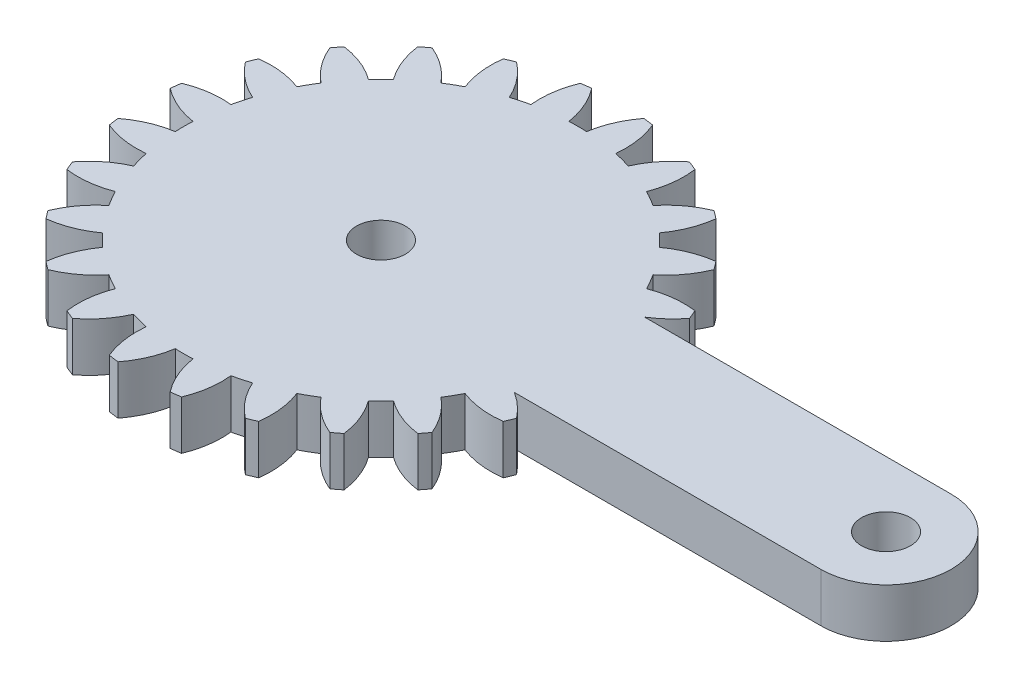
SolidWorks part; units mm, degrees
ref_plane "Front Plane" through (0, 0, 0) normal (0, 0, 1) x (1, 0, 0)
ref_plane "Top Plane" through (0, 0, 0) normal (0, 1, 0) x (1, 0, 0)
ref_plane "Right Plane" through (0, 0, 0) normal (1, 0, 0) x (0, 0, -1)
sketch "Sketch1" plane through (0, 0, 0) normal (0, 1, 0) x (1, 0, 0)
  line L0 (20.8937, 4) -> (2.0816, 4)
  line L1 (2.0816, -4) -> (20.8937, -4)
  line L2 (20.8937, 0) -> (-10.1063, 0) construction
  arc A0 (2.0816, 4) -> (3.5217, 5.3071) centre (-0.7683, 8.5867) ccw
  arc A1 (3.5217, 5.3071) -> (3.2829, 5.8838) centre (-10.1063, 0) ccw
  arc A2 (3.2829, 5.8838) -> (0.6271, 5.5703) centre (2.5684, 0.5313) ccw
  arc A3 (0.6271, 5.5703) -> (0.0844, 6.5103) centre (-10.1063, 0) ccw
  arc A4 (0.0844, 6.5103) -> (1.6838, 8.6535) centre (-3.3089, 10.711) ccw
  arc A5 (1.6838, 8.6535) -> (1.3038, 9.1487) centre (-10.1063, 0) ccw
  arc A6 (1.3038, 9.1487) -> (-1.1803, 8.1585) centre (1.999, 3.7936) ccw
  arc A7 (-1.1803, 8.1585) -> (-1.9479, 8.926) centre (-10.1063, 0) ccw
  arc A8 (-1.9479, 8.926) -> (-0.9576, 11.4102) centre (-6.3127, 12.1053) ccw
  arc A9 (-0.9576, 11.4102) -> (-1.4528, 11.7901) centre (-10.1063, 0) ccw
  arc A10 (-1.4528, 11.7901) -> (-3.596, 10.1907) centre (0.6046, 6.7975) ccw
  arc A11 (-3.596, 10.1907) -> (-4.5361, 10.7334) centre (-10.1063, 0) ccw
  arc A12 (-4.5361, 10.7334) -> (-4.2225, 13.3892) centre (-9.5751, 12.6747) ccw
  arc A13 (-4.2225, 13.3892) -> (-4.7992, 13.6281) centre (-10.1063, 0) ccw
  arc A14 (-4.7992, 13.6281) -> (-6.4554, 11.5285) centre (-1.5196, 9.3381) ccw
  arc A15 (-6.4554, 11.5285) -> (-7.5039, 11.8094) centre (-10.1063, 0) ccw
  arc A16 (-7.5039, 11.8094) -> (-7.8884, 14.4558) centre (-12.8736, 12.3803) ccw
  arc A17 (-7.8884, 14.4558) -> (-8.5072, 14.5373) centre (-10.1063, 0) ccw
  arc A18 (-8.5072, 14.5373) -> (-9.5636, 12.0806) centre (-4.2291, 11.2423) ccw
  arc A19 (-9.5636, 12.0806) -> (-10.6491, 12.0806) centre (-10.1063, 0) ccw
  arc A20 (-10.6491, 12.0806) -> (-11.7054, 14.5373) centre (-15.9836, 11.2423) ccw
  arc A21 (-11.7054, 14.5373) -> (-12.3243, 14.4558) centre (-10.1063, 0) ccw
  arc A22 (-12.3243, 14.4558) -> (-12.7088, 11.8094) centre (-7.3391, 12.3803) ccw
  arc A23 (-12.7088, 11.8094) -> (-13.7573, 11.5285) centre (-10.1063, 0) ccw
  arc A24 (-13.7573, 11.5285) -> (-15.4135, 13.6281) centre (-18.6931, 9.3381) ccw
  arc A25 (-15.4135, 13.6281) -> (-15.9901, 13.3892) centre (-10.1063, 0) ccw
  arc A26 (-15.9901, 13.3892) -> (-15.6766, 10.7334) centre (-10.6376, 12.6747) ccw
  arc A27 (-15.6766, 10.7334) -> (-16.6166, 10.1907) centre (-10.1063, 0) ccw
  arc A28 (-16.6166, 10.1907) -> (-18.7599, 11.7901) centre (-20.8173, 6.7975) ccw
  arc A29 (-18.7599, 11.7901) -> (-19.255, 11.4102) centre (-10.1063, 0) ccw
  arc A30 (-19.255, 11.4102) -> (-18.2648, 8.926) centre (-13.9, 12.1053) ccw
  arc A31 (-18.2648, 8.926) -> (-19.0324, 8.1585) centre (-10.1063, 0) ccw
  arc A32 (-19.0324, 8.1585) -> (-21.5165, 9.1487) centre (-22.2117, 3.7936) ccw
  arc A33 (-21.5165, 9.1487) -> (-21.8965, 8.6535) centre (-10.1063, 0) ccw
  arc A34 (-21.8965, 8.6535) -> (-20.2971, 6.5103) centre (-16.9038, 10.711) ccw
  arc A35 (-20.2971, 6.5103) -> (-20.8398, 5.5703) centre (-10.1063, 0) ccw
  arc A36 (-20.8398, 5.5703) -> (-23.4956, 5.8838) centre (-22.7811, 0.5313) ccw
  arc A37 (-23.4956, 5.8838) -> (-23.7344, 5.3071) centre (-10.1063, 0) ccw
  arc A38 (-23.7344, 5.3071) -> (-21.6348, 3.6509) centre (-19.4444, 8.5867) ccw
  arc A39 (-21.6348, 3.6509) -> (-21.9157, 2.6025) centre (-10.1063, 0) ccw
  arc A40 (-21.9157, 2.6025) -> (-24.5622, 2.2179) centre (-22.4867, -2.7673) ccw
  arc A41 (-24.5622, 2.2179) -> (-24.6437, 1.5991) centre (-10.1063, 0) ccw
  arc A42 (-24.6437, 1.5991) -> (-22.1869, 0.5427) centre (-21.3486, 5.8773) ccw
  arc A43 (-22.1869, 0.5427) -> (-22.1869, -0.5427) centre (-10.1063, 0) ccw
  arc A44 (-22.1869, -0.5427) -> (-24.6437, -1.5991) centre (-21.3486, -5.8773) ccw
  arc A45 (-24.6437, -1.5991) -> (-24.5622, -2.2179) centre (-10.1063, 0) ccw
  arc A46 (-24.5622, -2.2179) -> (-21.9157, -2.6025) centre (-22.4867, 2.7673) ccw
  arc A47 (-21.9157, -2.6025) -> (-21.6348, -3.6509) centre (-10.1063, 0) ccw
  arc A48 (-21.6348, -3.6509) -> (-23.7344, -5.3071) centre (-19.4444, -8.5867) ccw
  arc A49 (-23.7344, -5.3071) -> (-23.4956, -5.8838) centre (-10.1063, 0) ccw
  arc A50 (-23.4956, -5.8838) -> (-20.8398, -5.5703) centre (-22.7811, -0.5313) ccw
  arc A51 (-20.8398, -5.5703) -> (-20.2971, -6.5103) centre (-10.1063, 0) ccw
  arc A52 (-20.2971, -6.5103) -> (-21.8965, -8.6535) centre (-16.9038, -10.711) ccw
  arc A53 (-21.8965, -8.6535) -> (-21.5165, -9.1487) centre (-10.1063, 0) ccw
  arc A54 (-21.5165, -9.1487) -> (-19.0324, -8.1585) centre (-22.2117, -3.7936) ccw
  arc A55 (-19.0324, -8.1585) -> (-18.2648, -8.926) centre (-10.1063, 0) ccw
  arc A56 (-18.2648, -8.926) -> (-19.255, -11.4102) centre (-13.9, -12.1053) ccw
  arc A57 (-19.255, -11.4102) -> (-18.7599, -11.7901) centre (-10.1063, 0) ccw
  arc A58 (-18.7599, -11.7901) -> (-16.6166, -10.1907) centre (-20.8173, -6.7975) ccw
  arc A59 (-16.6166, -10.1907) -> (-15.6766, -10.7334) centre (-10.1063, 0) ccw
  arc A60 (-15.6766, -10.7334) -> (-15.9901, -13.3892) centre (-10.6376, -12.6747) ccw
  arc A61 (-15.9901, -13.3892) -> (-15.4135, -13.6281) centre (-10.1063, 0) ccw
  arc A62 (-15.4135, -13.6281) -> (-13.7573, -11.5285) centre (-18.6931, -9.3381) ccw
  arc A63 (-13.7573, -11.5285) -> (-12.7088, -11.8094) centre (-10.1063, 0) ccw
  arc A64 (-12.7088, -11.8094) -> (-12.3243, -14.4558) centre (-7.3391, -12.3803) ccw
  arc A65 (-12.3243, -14.4558) -> (-11.7054, -14.5373) centre (-10.1063, 0) ccw
  arc A66 (-11.7054, -14.5373) -> (-10.6491, -12.0806) centre (-15.9836, -11.2423) ccw
  arc A67 (-10.6491, -12.0806) -> (-9.5636, -12.0806) centre (-10.1063, 0) ccw
  arc A68 (-9.5636, -12.0806) -> (-8.5072, -14.5373) centre (-4.2291, -11.2423) ccw
  arc A69 (-8.5072, -14.5373) -> (-7.8884, -14.4558) centre (-10.1063, 0) ccw
  arc A70 (-7.8884, -14.4558) -> (-7.5039, -11.8094) centre (-12.8736, -12.3803) ccw
  arc A71 (-7.5039, -11.8094) -> (-6.4554, -11.5285) centre (-10.1063, 0) ccw
  arc A72 (-6.4554, -11.5285) -> (-4.7992, -13.6281) centre (-1.5196, -9.3381) ccw
  arc A73 (-4.7992, -13.6281) -> (-4.2225, -13.3892) centre (-10.1063, 0) ccw
  arc A74 (-4.2225, -13.3892) -> (-4.5361, -10.7334) centre (-9.5751, -12.6747) ccw
  arc A75 (-4.5361, -10.7334) -> (-3.596, -10.1907) centre (-10.1063, 0) ccw
  arc A76 (-3.596, -10.1907) -> (-1.4528, -11.7901) centre (0.6046, -6.7975) ccw
  arc A77 (-1.4528, -11.7901) -> (-0.9576, -11.4102) centre (-10.1063, 0) ccw
  arc A78 (-0.9576, -11.4102) -> (-1.9479, -8.926) centre (-6.3127, -12.1053) ccw
  arc A79 (-1.9479, -8.926) -> (-1.1803, -8.1585) centre (-10.1063, 0) ccw
  arc A80 (-1.1803, -8.1585) -> (1.3038, -9.1487) centre (1.999, -3.7936) ccw
  arc A81 (1.3038, -9.1487) -> (1.6838, -8.6535) centre (-10.1063, 0) ccw
  arc A82 (1.6838, -8.6535) -> (0.0844, -6.5103) centre (-3.3089, -10.711) ccw
  arc A83 (0.0844, -6.5103) -> (0.6271, -5.5703) centre (-10.1063, 0) ccw
  arc A84 (0.6271, -5.5703) -> (3.2829, -5.8838) centre (2.5684, -0.5313) ccw
  arc A85 (3.2829, -5.8838) -> (3.5217, -5.3071) centre (-10.1063, 0) ccw
  arc A86 (3.5217, -5.3071) -> (2.0816, -4) centre (-0.7683, -8.5867) ccw
  arc A87 (20.8937, -4) -> (20.8937, 4) centre (20.8937, 0) ccw
  circle A88 centre (-10.1063, 0) radius 1.5
  circle A89 centre (20.8937, 0) radius 1.5
  dimension "D1" = 3
  dimension "D2" = 3
  dimension "D3" = 31
extrude "Boss-Extrude1" add sketch "Sketch1" along normal blind 3
sketch "Sketch2" plane through (0, 3, 0) normal (0, 1, 0) x (1, 0, 0)
  line L0 (2.0816, -4) -> (1.3057, -4)
  line L1 (20.8937, 0) -> (-10.1063, 0) construction
  line L2 (20.8937, 4) -> (2.0816, 4)
  line L3 (2.0816, -4) -> (20.8937, -4)
  line L4 (20.8937, 4) -> (2.0816, 4)
  line L5 (2.0816, -4) -> (20.8937, -4)
  circle A0 centre (-10.1063, 0) radius 12.0927
  arc A88 (20.8937, -4) -> (20.8937, 4) centre (20.8937, 0) ccw
  arc A89 (2.0816, 4) -> (3.5217, 5.3071) centre (-0.7683, 8.5867) ccw
  arc A90 (3.5217, 5.3071) -> (3.2829, 5.8838) centre (-10.1063, 0) ccw
  arc A91 (3.2829, 5.8838) -> (0.6271, 5.5703) centre (2.5684, 0.5313) ccw
  arc A92 (0.6271, 5.5703) -> (0.0844, 6.5103) centre (-10.1063, 0) ccw
  arc A93 (0.0844, 6.5103) -> (1.6838, 8.6535) centre (-3.3089, 10.711) ccw
  arc A94 (1.6838, 8.6535) -> (1.3038, 9.1487) centre (-10.1063, 0) ccw
  arc A95 (1.3038, 9.1487) -> (-1.1803, 8.1585) centre (1.999, 3.7936) ccw
  arc A96 (-1.1803, 8.1585) -> (-1.9479, 8.926) centre (-10.1063, 0) ccw
  arc A97 (-1.9479, 8.926) -> (-0.9576, 11.4102) centre (-6.3127, 12.1053) ccw
  arc A98 (-0.9576, 11.4102) -> (-1.4528, 11.7901) centre (-10.1063, 0) ccw
  arc A99 (-1.4528, 11.7901) -> (-3.596, 10.1907) centre (0.6046, 6.7975) ccw
  arc A100 (-3.596, 10.1907) -> (-4.5361, 10.7334) centre (-10.1063, 0) ccw
  arc A101 (-4.5361, 10.7334) -> (-4.2225, 13.3892) centre (-9.5751, 12.6747) ccw
  arc A102 (-4.2225, 13.3892) -> (-4.7992, 13.6281) centre (-10.1063, 0) ccw
  arc A103 (-4.7992, 13.6281) -> (-6.4554, 11.5285) centre (-1.5196, 9.3381) ccw
  arc A104 (-6.4554, 11.5285) -> (-7.5039, 11.8094) centre (-10.1063, 0) ccw
  arc A105 (-7.5039, 11.8094) -> (-7.8884, 14.4558) centre (-12.8736, 12.3803) ccw
  arc A106 (-7.8884, 14.4558) -> (-8.5072, 14.5373) centre (-10.1063, 0) ccw
  arc A107 (-8.5072, 14.5373) -> (-9.5636, 12.0806) centre (-4.2291, 11.2423) ccw
  arc A108 (-9.5636, 12.0806) -> (-10.6491, 12.0806) centre (-10.1063, 0) ccw
  arc A109 (-10.6491, 12.0806) -> (-11.7054, 14.5373) centre (-15.9836, 11.2423) ccw
  arc A110 (-11.7054, 14.5373) -> (-12.3243, 14.4558) centre (-10.1063, 0) ccw
  arc A111 (-12.3243, 14.4558) -> (-12.7088, 11.8094) centre (-7.3391, 12.3803) ccw
  arc A112 (-12.7088, 11.8094) -> (-13.7573, 11.5285) centre (-10.1063, 0) ccw
  arc A113 (-13.7573, 11.5285) -> (-15.4135, 13.6281) centre (-18.6931, 9.3381) ccw
  arc A114 (-15.4135, 13.6281) -> (-15.9901, 13.3892) centre (-10.1063, 0) ccw
  arc A115 (-15.9901, 13.3892) -> (-15.6766, 10.7334) centre (-10.6376, 12.6747) ccw
  arc A116 (-15.6766, 10.7334) -> (-16.6166, 10.1907) centre (-10.1063, 0) ccw
  arc A117 (-16.6166, 10.1907) -> (-18.7599, 11.7901) centre (-20.8173, 6.7975) ccw
  arc A118 (-18.7599, 11.7901) -> (-19.255, 11.4102) centre (-10.1063, 0) ccw
  arc A119 (-19.255, 11.4102) -> (-18.2648, 8.926) centre (-13.9, 12.1053) ccw
  arc A120 (-18.2648, 8.926) -> (-19.0324, 8.1585) centre (-10.1063, 0) ccw
  arc A121 (-19.0324, 8.1585) -> (-21.5165, 9.1487) centre (-22.2117, 3.7936) ccw
  arc A122 (-21.5165, 9.1487) -> (-21.8965, 8.6535) centre (-10.1063, 0) ccw
  arc A123 (-21.8965, 8.6535) -> (-20.2971, 6.5103) centre (-16.9038, 10.711) ccw
  arc A124 (-20.2971, 6.5103) -> (-20.8398, 5.5703) centre (-10.1063, 0) ccw
  arc A125 (-20.8398, 5.5703) -> (-23.4956, 5.8838) centre (-22.7811, 0.5313) ccw
  arc A126 (-23.4956, 5.8838) -> (-23.7344, 5.3071) centre (-10.1063, 0) ccw
  arc A127 (-23.7344, 5.3071) -> (-21.6348, 3.6509) centre (-19.4444, 8.5867) ccw
  arc A128 (-21.6348, 3.6509) -> (-21.9157, 2.6025) centre (-10.1063, 0) ccw
  arc A129 (-21.9157, 2.6025) -> (-24.5622, 2.2179) centre (-22.4867, -2.7673) ccw
  arc A130 (-24.5622, 2.2179) -> (-24.6437, 1.5991) centre (-10.1063, 0) ccw
  arc A131 (-24.6437, 1.5991) -> (-22.1869, 0.5427) centre (-21.3486, 5.8773) ccw
  arc A132 (-22.1869, 0.5427) -> (-22.1869, -0.5427) centre (-10.1063, 0) ccw
  arc A133 (-22.1869, -0.5427) -> (-24.6437, -1.5991) centre (-21.3486, -5.8773) ccw
  arc A134 (-24.6437, -1.5991) -> (-24.5622, -2.2179) centre (-10.1063, 0) ccw
  arc A135 (-24.5622, -2.2179) -> (-21.9157, -2.6025) centre (-22.4867, 2.7673) ccw
  arc A136 (-21.9157, -2.6025) -> (-21.6348, -3.6509) centre (-10.1063, 0) ccw
  arc A137 (-21.6348, -3.6509) -> (-23.7344, -5.3071) centre (-19.4444, -8.5867) ccw
  arc A138 (-23.7344, -5.3071) -> (-23.4956, -5.8838) centre (-10.1063, 0) ccw
  arc A139 (-23.4956, -5.8838) -> (-20.8398, -5.5703) centre (-22.7811, -0.5313) ccw
  arc A140 (-20.8398, -5.5703) -> (-20.2971, -6.5103) centre (-10.1063, 0) ccw
  arc A141 (-20.2971, -6.5103) -> (-21.8965, -8.6535) centre (-16.9038, -10.711) ccw
  arc A142 (-21.8965, -8.6535) -> (-21.5165, -9.1487) centre (-10.1063, 0) ccw
  arc A143 (-21.5165, -9.1487) -> (-19.0324, -8.1585) centre (-22.2117, -3.7936) ccw
  arc A144 (-19.0324, -8.1585) -> (-18.2648, -8.926) centre (-10.1063, 0) ccw
  arc A145 (-18.2648, -8.926) -> (-19.255, -11.4102) centre (-13.9, -12.1053) ccw
  arc A146 (-19.255, -11.4102) -> (-18.7599, -11.7901) centre (-10.1063, 0) ccw
  arc A147 (-18.7599, -11.7901) -> (-16.6166, -10.1907) centre (-20.8173, -6.7975) ccw
  arc A148 (-16.6166, -10.1907) -> (-15.6766, -10.7334) centre (-10.1063, 0) ccw
  arc A149 (-15.6766, -10.7334) -> (-15.9901, -13.3892) centre (-10.6376, -12.6747) ccw
  arc A150 (-15.9901, -13.3892) -> (-15.4135, -13.6281) centre (-10.1063, 0) ccw
  arc A151 (-15.4135, -13.6281) -> (-13.7573, -11.5285) centre (-18.6931, -9.3381) ccw
  arc A152 (-13.7573, -11.5285) -> (-12.7088, -11.8094) centre (-10.1063, 0) ccw
  arc A153 (-12.7088, -11.8094) -> (-12.3243, -14.4558) centre (-7.3391, -12.3803) ccw
  arc A154 (-12.3243, -14.4558) -> (-11.7054, -14.5373) centre (-10.1063, 0) ccw
  arc A155 (-11.7054, -14.5373) -> (-10.6491, -12.0806) centre (-15.9836, -11.2423) ccw
  arc A156 (-10.6491, -12.0806) -> (-9.5636, -12.0806) centre (-10.1063, 0) ccw
  arc A157 (-9.5636, -12.0806) -> (-8.5072, -14.5373) centre (-4.2291, -11.2423) ccw
  arc A158 (-8.5072, -14.5373) -> (-7.8884, -14.4558) centre (-10.1063, 0) ccw
  arc A159 (-7.8884, -14.4558) -> (-7.5039, -11.8094) centre (-12.8736, -12.3803) ccw
  arc A160 (-7.5039, -11.8094) -> (-6.4554, -11.5285) centre (-10.1063, 0) ccw
  arc A161 (-6.4554, -11.5285) -> (-4.7992, -13.6281) centre (-1.5196, -9.3381) ccw
  arc A162 (-4.7992, -13.6281) -> (-4.2225, -13.3892) centre (-10.1063, 0) ccw
  arc A163 (-4.2225, -13.3892) -> (-4.5361, -10.7334) centre (-9.5751, -12.6747) ccw
  arc A164 (-4.5361, -10.7334) -> (-3.596, -10.1907) centre (-10.1063, 0) ccw
  arc A165 (-3.596, -10.1907) -> (-1.4528, -11.7901) centre (0.6046, -6.7975) ccw
  arc A166 (-1.4528, -11.7901) -> (-0.9576, -11.4102) centre (-10.1063, 0) ccw
  arc A167 (-0.9576, -11.4102) -> (-1.9479, -8.926) centre (-6.3127, -12.1053) ccw
  arc A168 (-1.9479, -8.926) -> (-1.1803, -8.1585) centre (-10.1063, 0) ccw
  arc A169 (-1.1803, -8.1585) -> (1.3038, -9.1487) centre (1.999, -3.7936) ccw
  arc A170 (1.3038, -9.1487) -> (1.6838, -8.6535) centre (-10.1063, 0) ccw
  arc A171 (1.6838, -8.6535) -> (0.0844, -6.5103) centre (-3.3089, -10.711) ccw
  arc A172 (0.0844, -6.5103) -> (0.6271, -5.5703) centre (-10.1063, 0) ccw
  arc A173 (0.6271, -5.5703) -> (3.2829, -5.8838) centre (2.5684, -0.5313) ccw
  arc A174 (3.2829, -5.8838) -> (3.5217, -5.3071) centre (-10.1063, 0) ccw
  arc A175 (3.5217, -5.3071) -> (2.0816, -4) centre (-0.7683, -8.5867) ccw
  arc A176 (20.8937, -4) -> (20.8937, 4) centre (20.8937, 0) ccw
  arc A177 (2.0816, 4) -> (3.5217, 5.3071) centre (-0.7683, 8.5867) ccw
  arc A178 (3.5217, 5.3071) -> (3.2829, 5.8838) centre (-10.1063, 0) ccw
  arc A179 (3.2829, 5.8838) -> (0.6271, 5.5703) centre (2.5684, 0.5313) ccw
  arc A180 (0.6271, 5.5703) -> (0.0844, 6.5103) centre (-10.1063, 0) ccw
  arc A181 (0.0844, 6.5103) -> (1.6838, 8.6535) centre (-3.3089, 10.711) ccw
  arc A182 (1.6838, 8.6535) -> (1.3038, 9.1487) centre (-10.1063, 0) ccw
  arc A183 (1.3038, 9.1487) -> (-1.1803, 8.1585) centre (1.999, 3.7936) ccw
  arc A184 (-1.1803, 8.1585) -> (-1.9479, 8.926) centre (-10.1063, 0) ccw
  arc A185 (-1.9479, 8.926) -> (-0.9576, 11.4102) centre (-6.3127, 12.1053) ccw
  arc A186 (-0.9576, 11.4102) -> (-1.4528, 11.7901) centre (-10.1063, 0) ccw
  arc A187 (-1.4528, 11.7901) -> (-3.596, 10.1907) centre (0.6046, 6.7975) ccw
  arc A188 (-3.596, 10.1907) -> (-4.5361, 10.7334) centre (-10.1063, 0) ccw
  arc A189 (-4.5361, 10.7334) -> (-4.2225, 13.3892) centre (-9.5751, 12.6747) ccw
  arc A190 (-4.2225, 13.3892) -> (-4.7992, 13.6281) centre (-10.1063, 0) ccw
  arc A191 (-4.7992, 13.6281) -> (-6.4554, 11.5285) centre (-1.5196, 9.3381) ccw
  arc A192 (-6.4554, 11.5285) -> (-7.5039, 11.8094) centre (-10.1063, 0) ccw
  arc A193 (-7.5039, 11.8094) -> (-7.8884, 14.4558) centre (-12.8736, 12.3803) ccw
  arc A194 (-7.8884, 14.4558) -> (-8.5072, 14.5373) centre (-10.1063, 0) ccw
  arc A195 (-8.5072, 14.5373) -> (-9.5636, 12.0806) centre (-4.2291, 11.2423) ccw
  arc A196 (-9.5636, 12.0806) -> (-10.6491, 12.0806) centre (-10.1063, 0) ccw
  arc A197 (-10.6491, 12.0806) -> (-11.7054, 14.5373) centre (-15.9836, 11.2423) ccw
  arc A198 (-11.7054, 14.5373) -> (-12.3243, 14.4558) centre (-10.1063, 0) ccw
  arc A199 (-12.3243, 14.4558) -> (-12.7088, 11.8094) centre (-7.3391, 12.3803) ccw
  arc A200 (-12.7088, 11.8094) -> (-13.7573, 11.5285) centre (-10.1063, 0) ccw
  arc A201 (-13.7573, 11.5285) -> (-15.4135, 13.6281) centre (-18.6931, 9.3381) ccw
  arc A202 (-15.4135, 13.6281) -> (-15.9901, 13.3892) centre (-10.1063, 0) ccw
  arc A203 (-15.9901, 13.3892) -> (-15.6766, 10.7334) centre (-10.6376, 12.6747) ccw
  arc A204 (-15.6766, 10.7334) -> (-16.6166, 10.1907) centre (-10.1063, 0) ccw
  arc A205 (-16.6166, 10.1907) -> (-18.7599, 11.7901) centre (-20.8173, 6.7975) ccw
  arc A206 (-18.7599, 11.7901) -> (-19.255, 11.4102) centre (-10.1063, 0) ccw
  arc A207 (-19.255, 11.4102) -> (-18.2648, 8.926) centre (-13.9, 12.1053) ccw
  arc A208 (-18.2648, 8.926) -> (-19.0324, 8.1585) centre (-10.1063, 0) ccw
  arc A209 (-19.0324, 8.1585) -> (-21.5165, 9.1487) centre (-22.2117, 3.7936) ccw
  arc A210 (-21.5165, 9.1487) -> (-21.8965, 8.6535) centre (-10.1063, 0) ccw
  arc A211 (-21.8965, 8.6535) -> (-20.2971, 6.5103) centre (-16.9038, 10.711) ccw
  arc A212 (-20.2971, 6.5103) -> (-20.8398, 5.5703) centre (-10.1063, 0) ccw
  arc A213 (-20.8398, 5.5703) -> (-23.4956, 5.8838) centre (-22.7811, 0.5313) ccw
  arc A214 (-23.4956, 5.8838) -> (-23.7344, 5.3071) centre (-10.1063, 0) ccw
  arc A215 (-23.7344, 5.3071) -> (-21.6348, 3.6509) centre (-19.4444, 8.5867) ccw
  arc A216 (-21.6348, 3.6509) -> (-21.9157, 2.6025) centre (-10.1063, 0) ccw
  arc A217 (-21.9157, 2.6025) -> (-24.5622, 2.2179) centre (-22.4867, -2.7673) ccw
  arc A218 (-24.5622, 2.2179) -> (-24.6437, 1.5991) centre (-10.1063, 0) ccw
  arc A219 (-24.6437, 1.5991) -> (-22.1869, 0.5427) centre (-21.3486, 5.8773) ccw
  arc A220 (-22.1869, 0.5427) -> (-22.1869, -0.5427) centre (-10.1063, 0) ccw
  arc A221 (-22.1869, -0.5427) -> (-24.6437, -1.5991) centre (-21.3486, -5.8773) ccw
  arc A222 (-24.6437, -1.5991) -> (-24.5622, -2.2179) centre (-10.1063, 0) ccw
  arc A223 (-24.5622, -2.2179) -> (-21.9157, -2.6025) centre (-22.4867, 2.7673) ccw
  arc A224 (-21.9157, -2.6025) -> (-21.6348, -3.6509) centre (-10.1063, 0) ccw
  arc A225 (-21.6348, -3.6509) -> (-23.7344, -5.3071) centre (-19.4444, -8.5867) ccw
  arc A226 (-23.7344, -5.3071) -> (-23.4956, -5.8838) centre (-10.1063, 0) ccw
  arc A227 (-23.4956, -5.8838) -> (-20.8398, -5.5703) centre (-22.7811, -0.5313) ccw
  arc A228 (-20.8398, -5.5703) -> (-20.2971, -6.5103) centre (-10.1063, 0) ccw
  arc A229 (-20.2971, -6.5103) -> (-21.8965, -8.6535) centre (-16.9038, -10.711) ccw
  arc A230 (-21.8965, -8.6535) -> (-21.5165, -9.1487) centre (-10.1063, 0) ccw
  arc A231 (-21.5165, -9.1487) -> (-19.0324, -8.1585) centre (-22.2117, -3.7936) ccw
  arc A232 (-19.0324, -8.1585) -> (-18.2648, -8.926) centre (-10.1063, 0) ccw
  arc A233 (-18.2648, -8.926) -> (-19.255, -11.4102) centre (-13.9, -12.1053) ccw
  arc A234 (-19.255, -11.4102) -> (-18.7599, -11.7901) centre (-10.1063, 0) ccw
  arc A235 (-18.7599, -11.7901) -> (-16.6166, -10.1907) centre (-20.8173, -6.7975) ccw
  arc A236 (-16.6166, -10.1907) -> (-15.6766, -10.7334) centre (-10.1063, 0) ccw
  arc A237 (-15.6766, -10.7334) -> (-15.9901, -13.3892) centre (-10.6376, -12.6747) ccw
  arc A238 (-15.9901, -13.3892) -> (-15.4135, -13.6281) centre (-10.1063, 0) ccw
  arc A239 (-15.4135, -13.6281) -> (-13.7573, -11.5285) centre (-18.6931, -9.3381) ccw
  arc A240 (-13.7573, -11.5285) -> (-12.7088, -11.8094) centre (-10.1063, 0) ccw
  arc A241 (-12.7088, -11.8094) -> (-12.3243, -14.4558) centre (-7.3391, -12.3803) ccw
  arc A242 (-12.3243, -14.4558) -> (-11.7054, -14.5373) centre (-10.1063, 0) ccw
  arc A243 (-11.7054, -14.5373) -> (-10.6491, -12.0806) centre (-15.9836, -11.2423) ccw
  arc A244 (-10.6491, -12.0806) -> (-9.5636, -12.0806) centre (-10.1063, 0) ccw
  arc A245 (-9.5636, -12.0806) -> (-8.5072, -14.5373) centre (-4.2291, -11.2423) ccw
  arc A246 (-8.5072, -14.5373) -> (-7.8884, -14.4558) centre (-10.1063, 0) ccw
  arc A247 (-7.8884, -14.4558) -> (-7.5039, -11.8094) centre (-12.8736, -12.3803) ccw
  arc A248 (-7.5039, -11.8094) -> (-6.4554, -11.5285) centre (-10.1063, 0) ccw
  arc A249 (-6.4554, -11.5285) -> (-4.7992, -13.6281) centre (-1.5196, -9.3381) ccw
  arc A250 (-4.7992, -13.6281) -> (-4.2225, -13.3892) centre (-10.1063, 0) ccw
  arc A251 (-4.2225, -13.3892) -> (-4.5361, -10.7334) centre (-9.5751, -12.6747) ccw
  arc A252 (-4.5361, -10.7334) -> (-3.596, -10.1907) centre (-10.1063, 0) ccw
  arc A253 (-3.596, -10.1907) -> (-1.4528, -11.7901) centre (0.6046, -6.7975) ccw
  arc A254 (-1.4528, -11.7901) -> (-0.9576, -11.4102) centre (-10.1063, 0) ccw
  arc A255 (-0.9576, -11.4102) -> (-1.9479, -8.926) centre (-6.3127, -12.1053) ccw
  arc A256 (-1.9479, -8.926) -> (-1.1803, -8.1585) centre (-10.1063, 0) ccw
  arc A257 (-1.1803, -8.1585) -> (1.3038, -9.1487) centre (1.999, -3.7936) ccw
  arc A258 (1.3038, -9.1487) -> (1.6838, -8.6535) centre (-10.1063, 0) ccw
  arc A259 (1.6838, -8.6535) -> (0.0844, -6.5103) centre (-3.3089, -10.711) ccw
  arc A260 (0.0844, -6.5103) -> (0.6271, -5.5703) centre (-10.1063, 0) ccw
  arc A261 (0.6271, -5.5703) -> (3.2829, -5.8838) centre (2.5684, -0.5313) ccw
  arc A262 (3.2829, -5.8838) -> (3.5217, -5.3071) centre (-10.1063, 0) ccw
  arc A263 (3.5217, -5.3071) -> (2.0816, -4) centre (-0.7683, -8.5867) ccw
  dimension "D1" = 0
scale "Scale1" scale about centroid uniform scaling yes scale factor 0.888889
